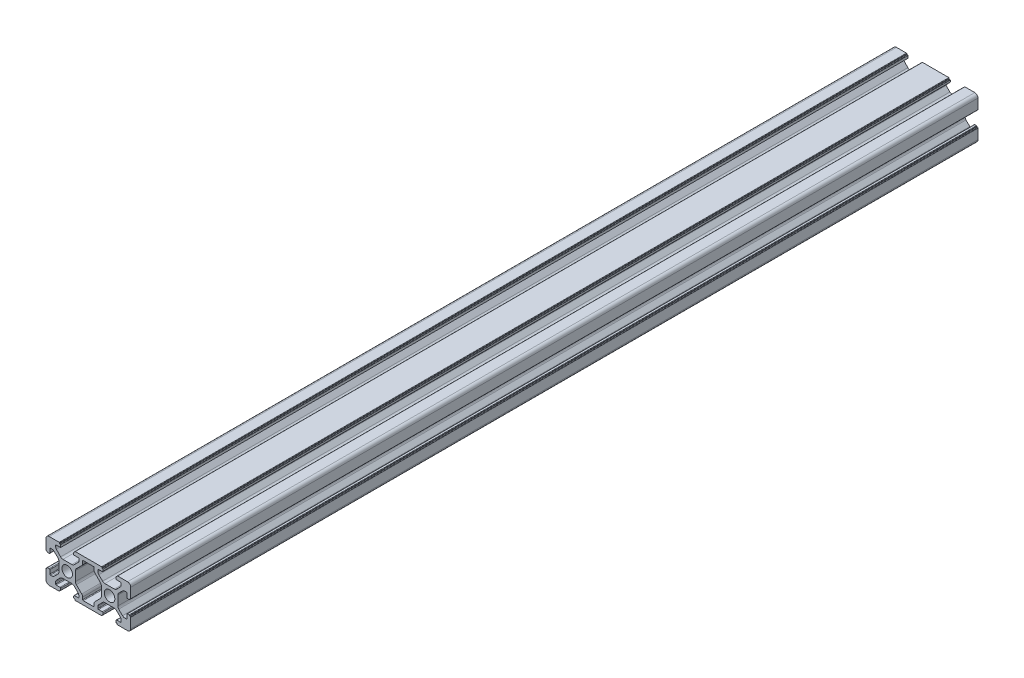
SolidWorks part; units mm, degrees
material "6063-O"
ref_plane "Front Plane" through (0, 0, 0) normal (0, 0, 1) x (1, 0, 0)
ref_plane "Top Plane" through (0, 0, 0) normal (0, 1, 0) x (1, 0, 0)
ref_plane "Right Plane" through (0, 0, 0) normal (1, 0, 0) x (0, 0, -1)
sketch "Sketch1" plane through (0, 0, 0) normal (0, 0, 1) x (1, 0, 0)
  line L0 (1.5, 0) -> (6.2, 0)
  line L1 (40, 1.5) -> (40, 6.2)
  line L2 (38.5, 20) -> (33.8, 20)
  line L3 (0, 18.5) -> (0, 13.8)
  line L4 (17.6, 1.8) -> (22.4, 1.8)
  line L5 (32.218, 13.9) -> (27.782, 13.9)
  line L6 (26.1, 12.218) -> (26.1, 7.782)
  line L7 (17.6, 18.2) -> (22.4, 18.2)
  line L8 (12.218, 13.9) -> (7.9864, 13.9)
  line L9 (6.1, 12.218) -> (6.1, 7.782)
  line L10 (7.782, 6.1) -> (12.218, 6.1)
  line L11 (13.9, 7.782) -> (13.9, 12.218)
  line L12 (27.782, 6.1) -> (32.218, 6.1)
  line L13 (33.9, 7.782) -> (33.9, 12.218)
  line L14 (26.7213, 14.3393) -> (24.9393, 16.1213)
  line L15 (33.2787, 14.3393) -> (35.0607, 16.1213)
  line L16 (34.3393, 13.2787) -> (36.1213, 15.0607)
  line L17 (25.6607, 6.7213) -> (23.1393, 4.2)
  line L18 (15.2, 1.8) -> (13.4, 1.8)
  line L19 (26.7213, 5.6607) -> (24.9393, 3.8787)
  line L20 (24.8, 1.8) -> (26.6, 1.8)
  line L21 (15.3, 18.2) -> (13.1, 18.2)
  line L22 (13.2787, 14.3393) -> (15.1607, 16.2213)
  line L23 (14.3393, 13.2787) -> (16.8607, 15.8)
  line L24 (5.6607, 6.7213) -> (3.8787, 4.9393)
  line L25 (6.7213, 5.6607) -> (4.9393, 3.8787)
  line L26 (6.897, 14.3689) -> (4.9106, 16.4674)
  line L27 (5.6607, 13.2787) -> (3.8787, 15.0607)
  line L28 (14.3393, 6.7213) -> (16.8607, 4.2)
  line L29 (13.2787, 5.6607) -> (15.0607, 3.8787)
  line L30 (24.8, 18.2) -> (26.6, 18.2)
  line L31 (25.6607, 13.2787) -> (23.1393, 15.8)
  line L32 (34.3393, 6.7213) -> (36.1213, 4.9393)
  line L33 (33.2787, 5.6607) -> (35.0607, 3.8787)
  line L34 (1.8, 15.2) -> (1.8, 13.4)
  line L35 (24.5, 2.1) -> (24.5, 2.818)
  line L36 (4.5, 2.1) -> (4.5, 2.818)
  line L37 (2.818, 4.5) -> (2.1, 4.5)
  line L38 (4.5, 17.9) -> (4.5, 17.4986)
  line L39 (2.818, 15.5) -> (2.1, 15.5)
  line L40 (15.6, 17.9) -> (15.6, 17.282)
  line L41 (15.5, 2.818) -> (15.5, 2.1)
  line L42 (38.2, 15.2) -> (38.2, 13.4)
  line L43 (35.5, 2.818) -> (35.5, 2.1)
  line L44 (37.182, 4.5) -> (37.9, 4.5)
  line L45 (35.5, 17.182) -> (35.5, 17.9)
  line L46 (37.182, 15.5) -> (37.9, 15.5)
  line L47 (17.3, 2.1) -> (17.3, 3.1393)
  line L48 (22.7, 2.1) -> (22.7, 3.1393)
  line L49 (17.3, 17.9) -> (17.3, 16.8607)
  line L50 (22.7, 17.9) -> (22.7, 16.8607)
  line L51 (24.5, 17.9) -> (24.5, 17.182)
  line L52 (6.9, 19.3) -> (6.9, 18.2)
  line L53 (13.1, 19.3) -> (13.1, 18.2)
  line L54 (6.9, 1.5) -> (6.9, 0.7)
  line L55 (13.1, 1.5) -> (13.1, 0.7)
  line L56 (13.8, 0) -> (26.2, 0)
  line L57 (6.6, 1.8) -> (4.8, 1.8)
  line L58 (6.9, 18.2) -> (4.8, 18.2)
  line L59 (6.2, 20) -> (1.5, 20)
  line L60 (39.3, 6.9) -> (38.5, 6.9)
  line L61 (39.3, 13.1) -> (38.5, 13.1)
  line L62 (1.5, 13.1) -> (0.7, 13.1)
  line L63 (1.5, 6.9) -> (0.7, 6.9)
  line L64 (0, 6.2) -> (0, 1.5)
  line L65 (1.8, 6.6) -> (1.8, 4.8)
  line L66 (38.2, 6.6) -> (38.2, 4.8)
  line L67 (40, 13.8) -> (40, 18.5)
  line L68 (33.1, 19.3) -> (33.1, 18.5)
  line L69 (26.9, 19.3) -> (26.9, 18.5)
  line L70 (26.9, 1.5) -> (26.9, 0.7)
  line L71 (33.1, 1.5) -> (33.1, 0.7)
  line L72 (33.8, 0) -> (38.5, 0)
  line L73 (33.4, 1.8) -> (35.2, 1.8)
  line L74 (26.2, 20) -> (13.8, 20)
  line L75 (33.4, 18.2) -> (35.2, 18.2)
  line L76 (6.7, 0.5) -> (6.6, 0.5)
  line L77 (6.4, 0.3) -> (6.4, 0.2)
  line L78 (13.3, 0.5) -> (13.4, 0.5)
  line L79 (13.6, 0.3) -> (13.6, 0.2)
  line L80 (26.7, 0.5) -> (26.6, 0.5)
  line L81 (26.4, 0.3) -> (26.4, 0.2)
  line L82 (33.3, 0.5) -> (33.4, 0.5)
  line L83 (33.6, 0.3) -> (33.6, 0.2)
  line L85 (6.4, 19.8) -> (6.4, 19.7)
  line L86 (6.6, 19.5) -> (6.7, 19.5)
  line L87 (13.6, 19.8) -> (13.6, 19.7)
  line L88 (13.4, 19.5) -> (13.3, 19.5)
  line L89 (26.4, 19.8) -> (26.4, 19.7)
  line L90 (26.6, 19.5) -> (26.7, 19.5)
  line L91 (33.6, 19.8) -> (33.6, 19.7)
  line L92 (33.4, 19.5) -> (33.3, 19.5)
  line L93 (0.5, 13.3) -> (0.5, 13.4)
  line L94 (0.3, 13.6) -> (0.2, 13.6)
  line L95 (0.5, 6.7) -> (0.5, 6.6)
  line L96 (0.3, 6.4) -> (0.2, 6.4)
  line L97 (39.5, 13.3) -> (39.5, 13.4)
  line L98 (39.7, 13.6) -> (39.8, 13.6)
  line L99 (39.5, 6.7) -> (39.5, 6.6)
  line L100 (39.7, 6.4) -> (39.8, 6.4)
  circle A0 centre (10, 10) radius 2.5
  circle A1 centre (30, 10) radius 2.5
  arc A2 (38.5, 0) -> (40, 1.5) centre (38.5, 1.5) ccw
  arc A3 (40, 18.5) -> (38.5, 20) centre (38.5, 18.5) ccw
  arc A4 (1.5, 0) -> (0, 1.5) centre (1.5, 1.5) cw
  arc A5 (1.5, 20) -> (0, 18.5) centre (1.5, 18.5) ccw
  arc A6 (26.7213, 5.6607) -> (27.782, 6.1) centre (27.782, 4.6) cw
  arc A7 (32.218, 6.1) -> (33.2787, 5.6607) centre (32.218, 4.6) cw
  arc A8 (33.9, 7.782) -> (34.3393, 6.7213) centre (35.4, 7.782) ccw
  arc A9 (33.2787, 14.3393) -> (32.218, 13.9) centre (32.218, 15.4) cw
  arc A10 (14.3393, 6.7213) -> (13.9, 7.782) centre (15.4, 7.782) cw
  arc A11 (14.3393, 13.2787) -> (13.9, 12.218) centre (15.4, 12.218) ccw
  arc A12 (25.6607, 6.7213) -> (26.1, 7.782) centre (24.6, 7.782) ccw
  arc A13 (26.1, 12.218) -> (25.6607, 13.2787) centre (24.6, 12.218) ccw
  arc A14 (27.782, 13.9) -> (26.7213, 14.3393) centre (27.782, 15.4) cw
  arc A15 (5.6607, 13.2787) -> (6.1, 12.218) centre (4.6, 12.218) cw
  arc A16 (5.6607, 6.7213) -> (6.1, 7.782) centre (4.6, 7.782) ccw
  arc A17 (13.2787, 5.6607) -> (12.218, 6.1) centre (12.218, 4.6) ccw
  arc A18 (6.7213, 5.6607) -> (7.782, 6.1) centre (7.782, 4.6) cw
  arc A19 (13.2787, 14.3393) -> (12.218, 13.9) centre (12.218, 15.4) cw
  arc A20 (6.897, 14.3689) -> (7.9864, 13.9) centre (7.9864, 15.4) ccw
  arc A21 (36.1213, 4.9393) -> (37.182, 4.5) centre (37.182, 6) ccw
  arc A22 (36.1213, 15.0607) -> (37.182, 15.5) centre (37.182, 14) cw
  arc A23 (35.0607, 16.1213) -> (35.5, 17.182) centre (34, 17.182) ccw
  arc A24 (24.5, 17.182) -> (24.9393, 16.1213) centre (26, 17.182) ccw
  arc A25 (22.7, 16.8607) -> (23.1393, 15.8) centre (24.2, 16.8607) ccw
  arc A26 (17.3, 16.8607) -> (16.8607, 15.8) centre (15.8, 16.8607) cw
  arc A27 (4.9106, 16.4674) -> (4.5, 17.4986) centre (6, 17.4986) cw
  arc A28 (15.6, 17.282) -> (15.1607, 16.2213) centre (14.1, 17.282) cw
  arc A29 (3.8787, 15.0607) -> (2.818, 15.5) centre (2.818, 14) ccw
  arc A30 (3.8787, 4.9393) -> (2.818, 4.5) centre (2.818, 6) cw
  arc A31 (4.9393, 3.8787) -> (4.5, 2.818) centre (6, 2.818) ccw
  arc A32 (35.0607, 3.8787) -> (35.5, 2.818) centre (34, 2.818) cw
  arc A33 (24.9393, 3.8787) -> (24.5, 2.818) centre (26, 2.818) ccw
  arc A34 (22.7, 3.1393) -> (23.1393, 4.2) centre (24.2, 3.1393) cw
  arc A35 (17.3, 3.1393) -> (16.8607, 4.2) centre (15.8, 3.1393) ccw
  arc A36 (15.5, 2.818) -> (15.0607, 3.8787) centre (14, 2.818) ccw
  arc A37 (1.8, 6.6) -> (1.5, 6.9) centre (1.5, 6.6) ccw
  arc A38 (1.8, 13.4) -> (1.5, 13.1) centre (1.5, 13.4) cw
  arc A39 (17.6, 18.2) -> (17.3, 17.9) centre (17.6, 17.9) ccw
  arc A40 (22.4, 1.8) -> (22.7, 2.1) centre (22.4, 2.1) ccw
  arc A41 (17.6, 1.8) -> (17.3, 2.1) centre (17.6, 2.1) cw
  arc A42 (15.2, 1.8) -> (15.5, 2.1) centre (15.2, 2.1) ccw
  arc A43 (6.6, 1.8) -> (6.9, 1.5) centre (6.6, 1.5) cw
  arc A44 (13.4, 1.8) -> (13.1, 1.5) centre (13.4, 1.5) ccw
  arc A45 (24.8, 1.8) -> (24.5, 2.1) centre (24.8, 2.1) cw
  arc A46 (35.2, 1.8) -> (35.5, 2.1) centre (35.2, 2.1) ccw
  arc A47 (26.6, 1.8) -> (26.9, 1.5) centre (26.6, 1.5) cw
  arc A48 (33.4, 1.8) -> (33.1, 1.5) centre (33.4, 1.5) ccw
  arc A49 (26.9, 18.5) -> (26.6, 18.2) centre (26.6, 18.5) cw
  arc A50 (33.1, 18.5) -> (33.4, 18.2) centre (33.4, 18.5) ccw
  arc A51 (37.9, 4.5) -> (38.2, 4.8) centre (37.9, 4.8) ccw
  arc A52 (38.5, 13.1) -> (38.2, 13.4) centre (38.5, 13.4) cw
  arc A53 (38.5, 6.9) -> (38.2, 6.6) centre (38.5, 6.6) ccw
  arc A54 (38.2, 15.2) -> (37.9, 15.5) centre (37.9, 15.2) ccw
  arc A55 (35.2, 18.2) -> (35.5, 17.9) centre (35.2, 17.9) cw
  arc A56 (24.8, 18.2) -> (24.5, 17.9) centre (24.8, 17.9) ccw
  arc A57 (22.4, 18.2) -> (22.7, 17.9) centre (22.4, 17.9) cw
  arc A58 (15.3, 18.2) -> (15.6, 17.9) centre (15.3, 17.9) cw
  arc A59 (4.5, 17.9) -> (4.8, 18.2) centre (4.8, 17.9) cw
  arc A60 (1.8, 15.2) -> (2.1, 15.5) centre (2.1, 15.2) cw
  arc A61 (1.8, 4.8) -> (2.1, 4.5) centre (2.1, 4.8) ccw
  arc A62 (4.5, 2.1) -> (4.8, 1.8) centre (4.8, 2.1) ccw
  arc A63 (34.3393, 13.2787) -> (33.9, 12.218) centre (35.4, 12.218) ccw
  arc A64 (6.4, 0.2) -> (6.2, 0) centre (6.2, 0.2) cw
  arc A65 (6.6, 0.5) -> (6.4, 0.3) centre (6.6, 0.3) ccw
  arc A66 (6.7, 0.5) -> (6.9, 0.7) centre (6.7, 0.7) ccw
  arc A67 (13.6, 0.2) -> (13.8, 0) centre (13.8, 0.2) ccw
  arc A68 (13.4, 0.5) -> (13.6, 0.3) centre (13.4, 0.3) cw
  arc A69 (13.3, 0.5) -> (13.1, 0.7) centre (13.3, 0.7) cw
  arc A70 (26.4, 0.2) -> (26.2, 0) centre (26.2, 0.2) cw
  arc A71 (26.6, 0.5) -> (26.4, 0.3) centre (26.6, 0.3) ccw
  arc A72 (26.7, 0.5) -> (26.9, 0.7) centre (26.7, 0.7) ccw
  arc A73 (33.6, 0.2) -> (33.8, 0) centre (33.8, 0.2) ccw
  arc A74 (33.4, 0.5) -> (33.6, 0.3) centre (33.4, 0.3) cw
  arc A75 (33.3, 0.5) -> (33.1, 0.7) centre (33.3, 0.7) cw
  arc A76 (39.8, 6.4) -> (40, 6.2) centre (39.8, 6.2) cw
  arc A77 (39.5, 6.6) -> (39.7, 6.4) centre (39.7, 6.6) ccw
  arc A78 (39.5, 6.7) -> (39.3, 6.9) centre (39.3, 6.7) ccw
  arc A79 (39.5, 13.3) -> (39.3, 13.1) centre (39.3, 13.3) cw
  arc A80 (39.5, 13.4) -> (39.7, 13.6) centre (39.7, 13.4) cw
  arc A81 (39.8, 13.6) -> (40, 13.8) centre (39.8, 13.8) ccw
  arc A82 (33.3, 19.5) -> (33.1, 19.3) centre (33.3, 19.3) ccw
  arc A83 (33.6, 19.7) -> (33.4, 19.5) centre (33.4, 19.7) cw
  arc A84 (33.6, 19.8) -> (33.8, 20) centre (33.8, 19.8) cw
  arc A85 (26.7, 19.5) -> (26.9, 19.3) centre (26.7, 19.3) cw
  arc A86 (26.4, 19.7) -> (26.6, 19.5) centre (26.6, 19.7) ccw
  arc A87 (26.4, 19.8) -> (26.2, 20) centre (26.2, 19.8) ccw
  arc A88 (0.2, 6.4) -> (0, 6.2) centre (0.2, 6.2) ccw
  arc A89 (0.5, 6.6) -> (0.3, 6.4) centre (0.3, 6.6) cw
  arc A90 (0.5, 6.7) -> (0.7, 6.9) centre (0.7, 6.7) cw
  arc A91 (13.3, 19.5) -> (13.1, 19.3) centre (13.3, 19.3) ccw
  arc A92 (13.6, 19.7) -> (13.4, 19.5) centre (13.4, 19.7) cw
  arc A93 (13.6, 19.8) -> (13.8, 20) centre (13.8, 19.8) cw
  arc A94 (6.2, 20) -> (6.4, 19.8) centre (6.2, 19.8) cw
  arc A95 (6.7, 19.5) -> (6.9, 19.3) centre (6.7, 19.3) cw
  arc A96 (6.4, 19.7) -> (6.6, 19.5) centre (6.6, 19.7) ccw
  arc A97 (0.5, 13.3) -> (0.7, 13.1) centre (0.7, 13.3) ccw
  arc A98 (0.2, 13.6) -> (0, 13.8) centre (0.2, 13.8) cw
  arc A99 (0.5, 13.4) -> (0.3, 13.6) centre (0.3, 13.4) ccw
  point P87 (0, 0)
  point P178 (1.8, 6.9)
  point P181 (1.8, 13.1)
  point P186 (22.7, 1.8)
  point P193 (6.9, 1.8)
  point P204 (33.1, 1.8)
  point P209 (33.1, 18.2)
  point P216 (38.2, 6.9)
  point P243 (6.9, 0.5)
  point P248 (13.6, 0.5)
  point P257 (26.9, 0.5)
extrude "Boss-Extrude2" add sketch "Sketch1" along normal blind 400 contours A57 L7 A39 L49 A26 L23 A11 L11 A10 L28 A35 L47 A41 L4 A40 L48 A34 L17 A12 L6 A13 L31 A25 L50 | A0 | A1 | L59 A5 L3 A98 L94 A99 L93 A97 L62 A38 L34 A60 L39 A29 L27 A15 L9 A16 L24 A30 L37 A61 L65 A37 L63 A90 L95 A89 L96 A88 L64 A4 L0 A64 L77 A65 L76 A66 L54 A43 L57 A62 L36 A31 L25 A18 L10 A17 L29 A36 L41 A42 L18 A44 L55 A69 L78 A68 L79 A67 L56 A70 L81 A71 L80 A72 L70 A47 L20 A45 L35 A33 L19 A6 L12 A7 L33 A32 L43 A46 L73 A48 L71 A75 L82 A74 L83 A73 L72 A2 L1 A76 L100 A77 L99 A78 L60 A53 L66 A51 L44 A21 L32 A8 L13 A63 L16 A22 L46 A54 L42 A52 L61 A79 L97 A80 L98 A81 L67 A3 L2 A84 L91 A83 L92 A82 L68 A50 L75 A55 L45 A23 L15 A9 L5 A14 L14 A24 L51 A56 L30 A49 L69 A85 L90 A86 L89 A87 L74 A93 L87 A92 L88 A91 L53 L21 A58 L40 A28 L22 A19 L8 A20 L26 A27 L38 A59 L58 L52 A95 L86 A96 L85 A94
